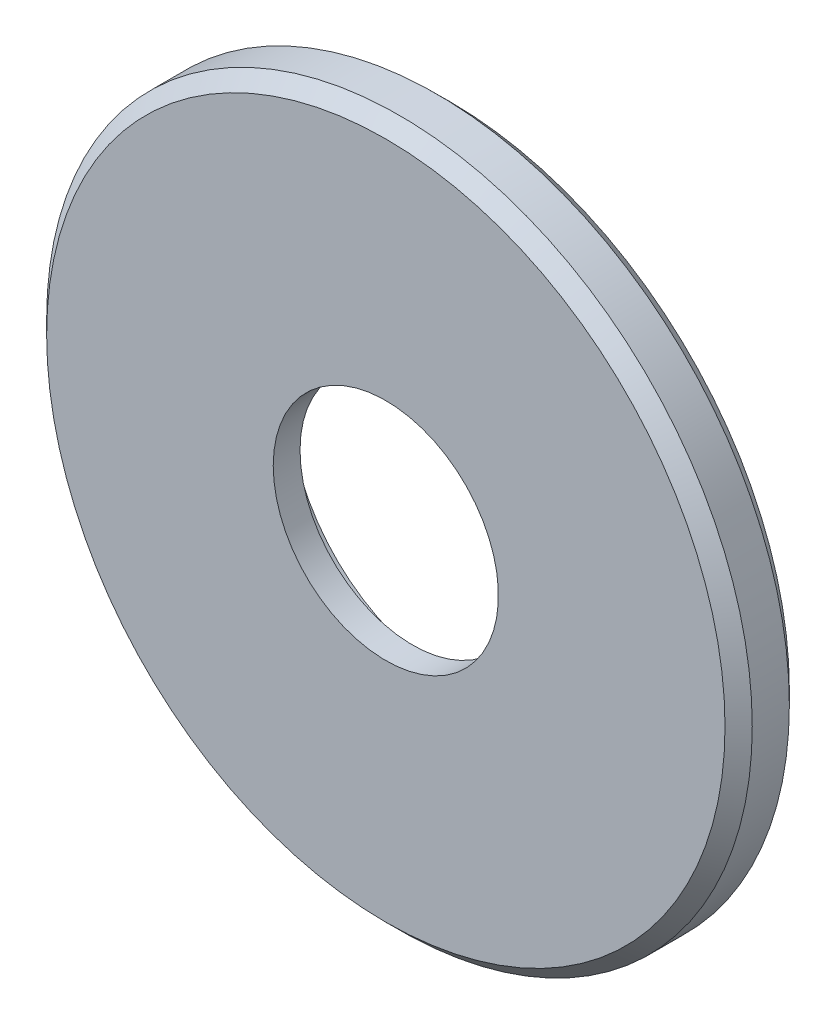
SolidWorks part; units mm, degrees
ref_plane "Plan de face" through (0, 0, 0) normal (0, 0, 1) x (1, 0, 0)
ref_plane "Plan de dessus" through (0, 0, 0) normal (0, 1, 0) x (1, 0, 0)
ref_plane "Plan de droite" through (0, 0, 0) normal (1, 0, 0) x (0, 0, -1)
sketch "Esquisse1" plane through (0, 0, 0) normal (0, 0, 1) x (1, 0, 0)
  circle A0 centre (0, 0) radius 65.7942
  dimension "D1" = 131.5884
extrude "Boss.-Extru.1" add sketch "Esquisse1" along normal blind 12
fillet "Congé1" radius 2.54 2 edges at (65.7942, 0, 0) (65.7942, 0, 12) profile chamfer
sketch "Esquisse2" plane through (0, 0, 0) normal (0, 0, -1) x (-1, 0, 0)
  circle A2 centre (0, 0) radius 21
  point P0 (0, 0)
  dimension "D1" = 42
sketch "Esquisse4" plane through (0, 0, 0) normal (0, 0, -1) x (-1, 0, 0)
  circle A1 centre (0.5511, 48.3556) radius 10.5
  circle A7 centre (42.1527, 23.7005) radius 10.5
  circle A8 centre (41.6016, -24.6551) radius 10.5
  circle A9 centre (-0.5511, -48.3556) radius 10.5
  circle A10 centre (-42.1527, -23.7005) radius 10.5
  circle A11 centre (-41.6016, 24.6551) radius 10.5
  point P14 (0.5511, 0.3556)
  point P16 (0, 0)
  dimension "D1" = 21
  dimension "D2" = 48
  dimension "D3" = 6
extrude "Enlèv. mat.-Extru.2" cut sketch "Esquisse4" against normal blind 5
extrude "Enlèv. mat.-Extru.4" cut sketch "Esquisse2" against normal through all
sketch "Esquisse5" plane through (0, 0, 0) normal (0, 0, -1) x (-1, 0, 0)
  circle A0 centre (0, 0) radius 30
  dimension "D1" = 60
extrude "Enlèv. mat.-Extru.5" cut sketch "Esquisse5" against normal blind 7
